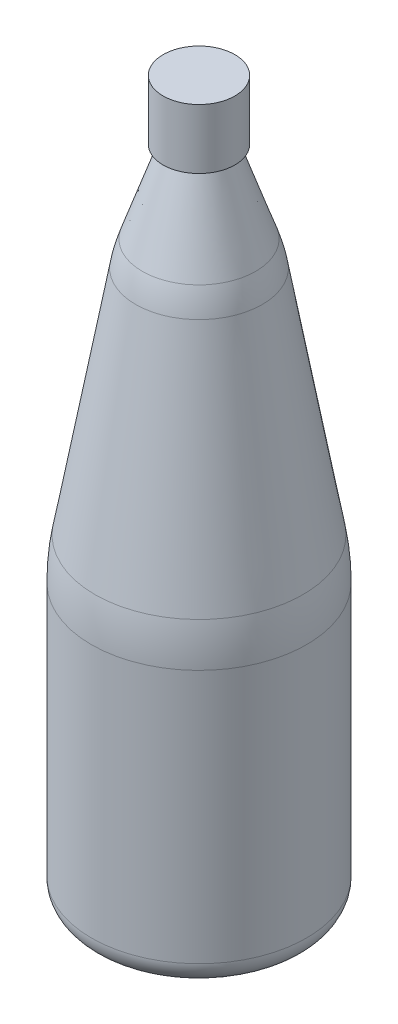
SolidWorks part; units mm, degrees
ref_plane "Front Plane" through (0, 0, 0) normal (0, 0, 1) x (1, 0, 0)
ref_plane "Top Plane" through (0, 0, 0) normal (0, 1, 0) x (1, 0, 0)
ref_plane "Right Plane" through (0, 0, 0) normal (1, 0, 0) x (0, 0, -1)
sketch "Sketch1" plane through (0, 0, 0) normal (0, 1, 0) x (1, 0, 0)
  circle A0 centre (0, 0) radius 45
  dimension "D1" = 90
extrude "Boss-Extrude1" add sketch "Sketch1" along normal blind 275
fillet "Fillet1" radius 10 1 edges at (0, 0, 45)
chamfer "Chamfer1" distance 150 angle 10 1 edges at (0, 275, 45)
fillet "Fillet2" radius 100 1 edges at (0, 125, 45)
chamfer "Chamfer2" distance 40 angle 9 1 edges at (0, 275, 18.551)
fillet "Fillet3" radius 70 1 edges at (0, 235.6077, 25.4969)
sketch "Sketch2" plane through (0, 275, 0) normal (0, 1, 0) x (1, 0, 0)
  circle A0 centre (0, 0) radius 15
  dimension "D1" = 30
extrude "Boss-Extrude2" add sketch "Sketch2" along normal blind 25
